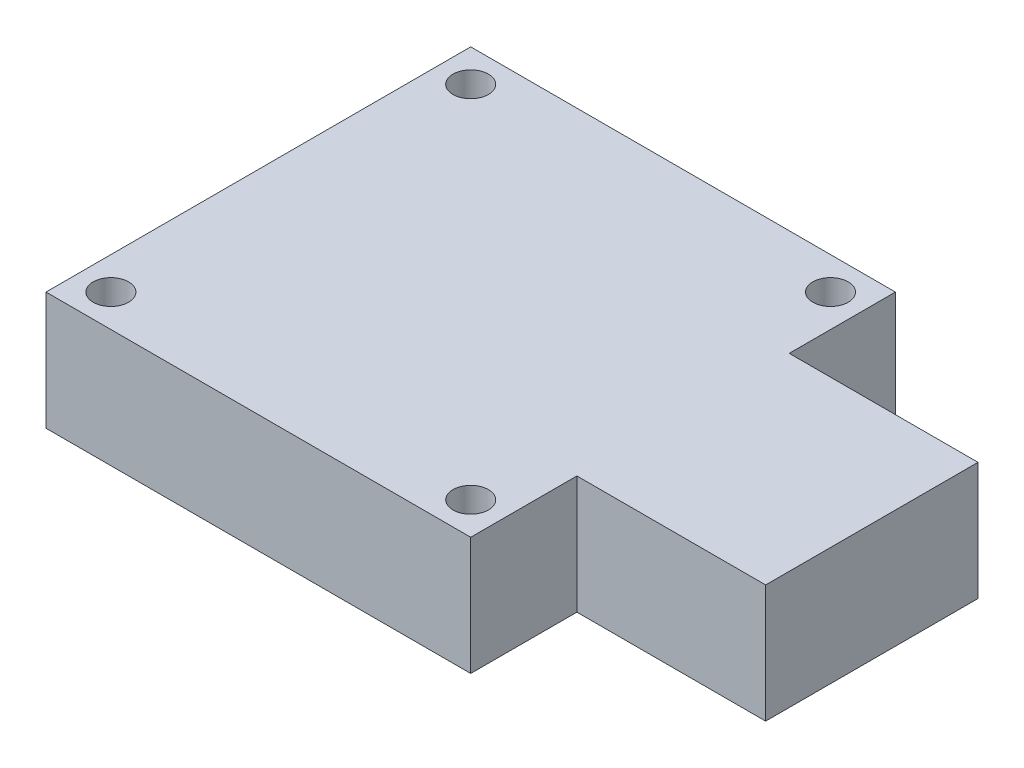
SolidWorks part; units mm, degrees
ref_plane "Front Plane" through (0, 0, 0) normal (0, 0, 1) x (1, 0, 0)
ref_plane "Top Plane" through (0, 0, 0) normal (0, 1, 0) x (1, 0, 0)
ref_plane "Right Plane" through (0, 0, 0) normal (1, 0, 0) x (0, 0, -1)
sketch "Sketch1" plane through (0, 0, 0) normal (0, 1, 0) x (1, 0, 0)
  line L0 (18, -9) -> (18, -18)
  line L1 (-18, 18) -> (18, 18)
  line L2 (-18, 18) -> (-18, -18)
  line L3 (-18, -18) -> (18, -18)
  line L4 (18, 18) -> (18, 9)
  line L5 (-18, 18) -> (18, -18) construction
  line L6 (-18, -18) -> (18, 18) construction
  line L7 (18, 9) -> (34, 9)
  line L9 (18, -9) -> (34, -9)
  line L10 (34, 9) -> (34, -9)
  line L11 (18, 9) -> (34, -9) construction
  line L12 (18, -9) -> (34, 9) construction
  point P0 (0, 0)
  point P6 (26, 0)
  dimension "D1" = 36
  dimension "D2" = 36
  dimension "D3" = 16
  dimension "D4" = 18
extrude "Boss-Extrude1" add sketch "Sketch1" along normal blind 10
sketch "Sketch2" plane through (0, 10, 0) normal (0, 1, 0) x (1, 0, 0)
  circle A0 centre (-15.25, 15.25) radius 1.5
  circle A1 centre (15.25, 15.25) radius 1.5
  circle A2 centre (-15.25, -15.25) radius 1.5
  circle A3 centre (15.25, -15.25) radius 1.5
  point P8 (0, 0)
  point P9 (0, 0)
  point P10 (0, 0)
  dimension "D1" = 3
  dimension "D4" = 15.25
  dimension "D2" = 30.5
  dimension "D3" = 30.5
  dimension "D5" = 15.25
extrude "Cut-Extrude1" cut sketch "Sketch2" against normal blind 10
